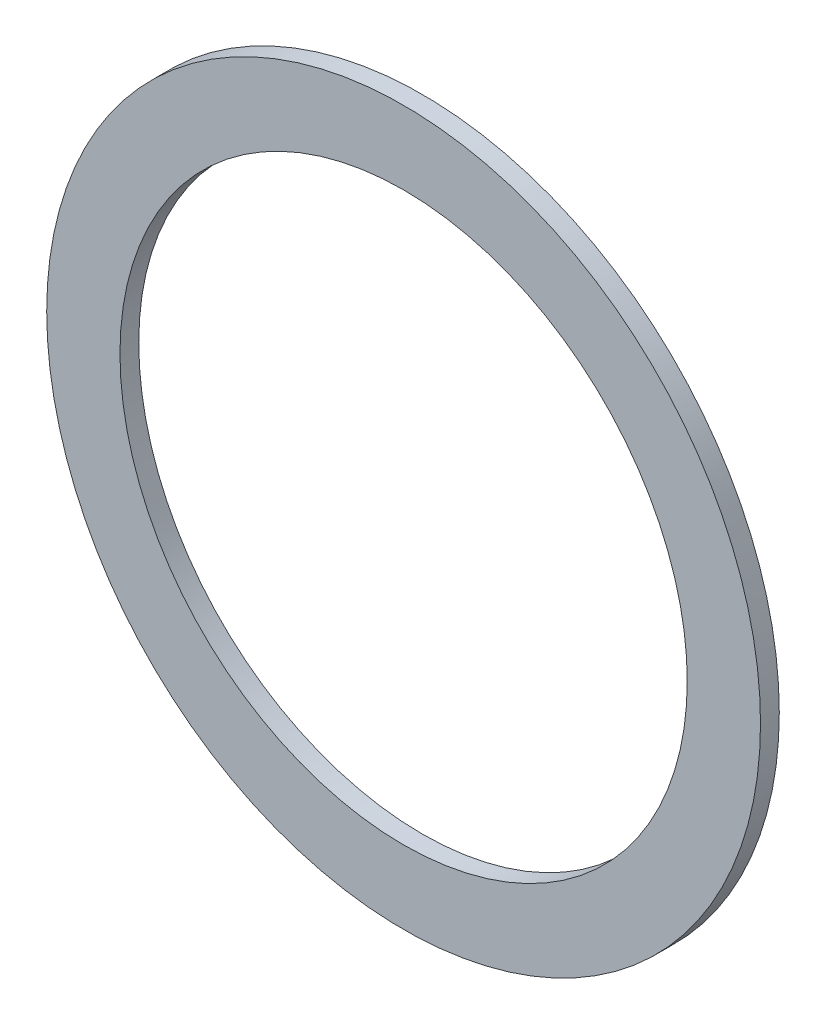
SolidWorks part; units mm, degrees
ref_plane "Front Plane" through (0, 0, 0) normal (0, 0, 1) x (1, 0, 0)
ref_plane "Top Plane" through (0, 0, 0) normal (0, 1, 0) x (1, 0, 0)
ref_plane "Right Plane" through (0, 0, 0) normal (1, 0, 0) x (0, 0, -1)
sketch "Sketch1" plane through (0, 0, 0) normal (0, 0, 1) x (1, 0, 0)
  circle A0 centre (0, 0) radius 15.1
  circle A1 centre (0, 0) radius 19
  dimension "D1" = 30.2
  dimension "D2" = 38
extrude "Boss-Extrude1" add sketch "Sketch1" along normal mid plane 1 contours A0 | A1
